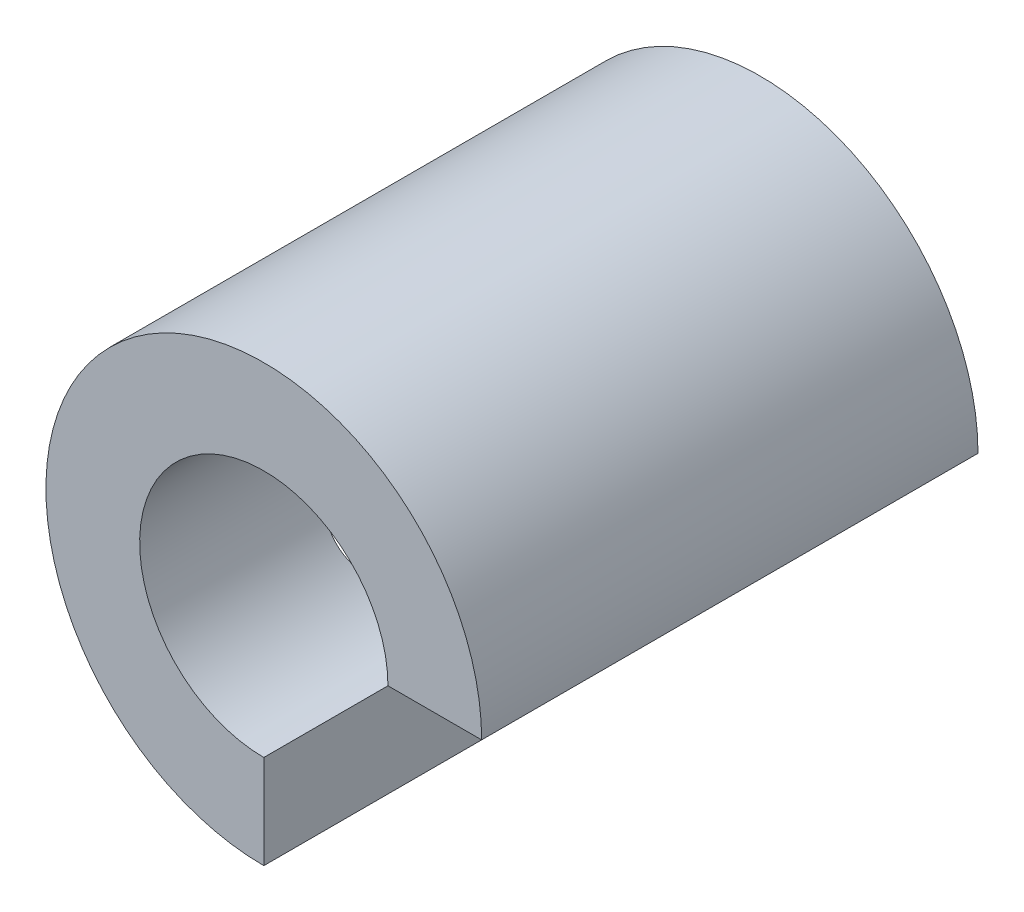
SolidWorks part; units mm, degrees
ref_plane "Front Plane" through (0, 0, 0) normal (0, 0, 1) x (1, 0, 0)
ref_plane "Top Plane" through (0, 0, 0) normal (0, 1, 0) x (1, 0, 0)
ref_plane "Right Plane" through (0, 0, 0) normal (1, 0, 0) x (0, 0, -1)
sketch "Sketch1" plane through (0, 0, 0) normal (0, 0, 1) x (1, 0, 0)
  line L0 (0, -1.115) -> (0, -0.6354)
  line L1 (1.115, 0) -> (0.6354, 0)
  arc A0 (1.115, 0) -> (0, -1.115) centre (0, 0) ccw
  arc A3 (0.6354, 0) -> (0, -0.6354) centre (0, 0) ccw
  dimension "D1" = 0.6354
extrude "Boss-Extrude1" add sketch "Sketch1" along normal blind 2.54
hole_wizard "1/32 (0.03125) Diameter Hole1" positions "3DSketch5" profile "Sketch6" hole size "1/32" standard "ANSI Inch"
sketch3d "3DSketch5"
  point P0 (-0.9299, -0.6151, 1.2663)
sketch "Sketch6" plane through (-0.9299, -0.6151, 1.2663) normal (0, 0, 1) x (0.5517, -0.834, 0)
  line L0 (0, 0) -> (0, 1.603)
  line L1 (0, 1.603) -> (0.3969, 1.27)
  line L2 (0.3969, 1.27) -> (0.3969, 0)
  line L5 (0.3969, 0) -> (0, 0)
  line L10 (0, 1.603) -> (-0.3969, 1.27) construction
  line L11 (0, -6.35) -> (0, 107.95) construction
  dimension "Hole Dia." = 0.7937
  dimension "Hole Depth" = 1.27
  dimension "Drill Angle" = 100
